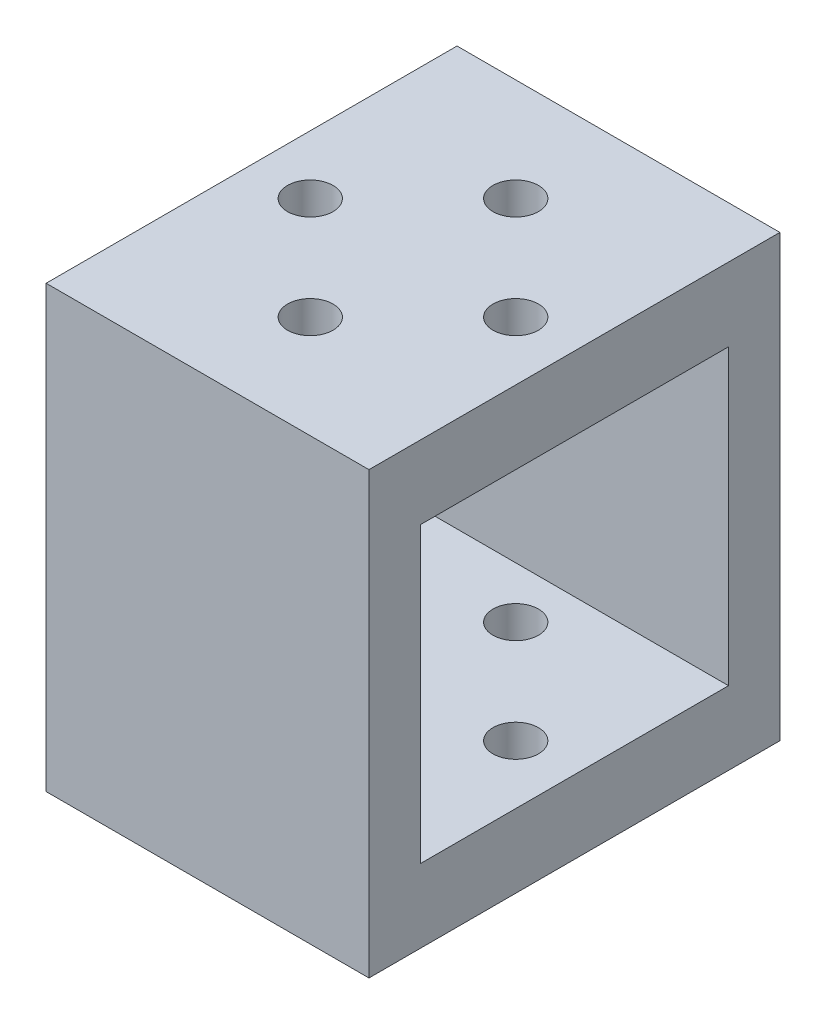
SolidWorks part; units mm, degrees
ref_plane "Front Plane" through (0, 0, 0) normal (0, 0, 1) x (1, 0, 0)
ref_plane "Top Plane" through (0, 0, 0) normal (0, 1, 0) x (1, 0, 0)
ref_plane "Right Plane" through (0, 0, 0) normal (1, 0, 0) x (0, 0, -1)
sketch "Sketch1" plane through (0, 0, 0) normal (0, 1, 0) x (1, 0, 0)
  line L1 (-11, 14) -> (11, 14)
  line L2 (-11, 14) -> (-11, -14)
  line L3 (-11, -14) -> (11, -14)
  line L4 (11, 14) -> (11, -14)
  line L5 (-11, 14) -> (11, -14) construction
  line L6 (-11, -14) -> (11, 14) construction
  point P0 (0, 0)
  dimension "D1" = 28
  dimension "D2" = 22
extrude "Boss-Extrude1" add sketch "Sketch1" along normal blind 5
sketch "Sketch2" plane through (0, 5, 0) normal (0, 1, 0) x (1, 0, 0)
  line L0 (11, -14) -> (11, 14) construction
  line L1 (-11, -14) -> (11, -14)
  line L2 (-11, -14) -> (-11, -9)
  line L3 (-11, -9) -> (11, -9)
  line L4 (11, -14) -> (11, -9)
  line L5 (-11, 0) -> (11, 0) construction
  line L6 (-11, 14) -> (-11, -14) construction
  line L7 (11, 14) -> (11, 9)
  line L8 (-11, 9) -> (11, 9)
  line L9 (-11, 14) -> (-11, 9)
  line L10 (-11, 14) -> (11, 14)
  dimension "D1" = 5
extrude "Boss-Extrude2" add sketch "Sketch2" along normal blind 20
sketch "Sketch3" plane through (0, 25, 0) normal (0, 1, 0) x (1, 0, 0)
  line L1 (-11, 14) -> (11, 14)
  line L2 (-11, 14) -> (-11, -14)
  line L3 (-11, -14) -> (11, -14)
  line L4 (11, 14) -> (11, -14)
  line L5 (-11, 14) -> (11, -14) construction
  line L6 (-11, -14) -> (11, 14) construction
  point P0 (0, 0)
extrude "Boss-Extrude3" add sketch "Sketch3" along normal blind 5
sketch "Sketch4" plane through (0, 30, 0) normal (0, 1, 0) x (1, 0, 0)
  line L0 (-11, 0) -> (0, 0) construction
  line L1 (-11, 14) -> (-11, -14) construction
  line L2 (0, 0) -> (0, 14) construction
  line L3 (11, 14) -> (-11, 14) construction
  circle A0 centre (0, 7) radius 1.55
  circle A1 centre (7, 0) radius 1.55
  circle A2 centre (0, -7) radius 1.55
  circle A3 centre (-7, 0) radius 1.55
  dimension "D1" = 3.1
  dimension "D3" = 4
  dimension "D2" = 7
extrude "Cut-Extrude1" cut sketch "Sketch4" against normal blind 30
sketch "Sketch5" plane through (0, 0, -9) normal (0, 0, 1) x (1, 0, 0)
  line L1 (11, 5) -> (-11, 5)
  line L2 (11, 5) -> (11, 25)
  line L3 (11, 25) -> (-11, 25)
  line L4 (-11, 5) -> (-11, 25)
extrude "Cut-Extrude2" cut sketch "Sketch5" against normal blind 1.5
sketch "Sketch6" plane through (0, 0, 9) normal (0, 0, -1) x (-1, 0, 0)
  line L1 (-11, 5) -> (11, 5)
  line L2 (-11, 5) -> (-11, 25)
  line L3 (-11, 25) -> (11, 25)
  line L4 (11, 5) -> (11, 25)
extrude "Cut-Extrude3" cut sketch "Sketch6" against normal blind 1.5
